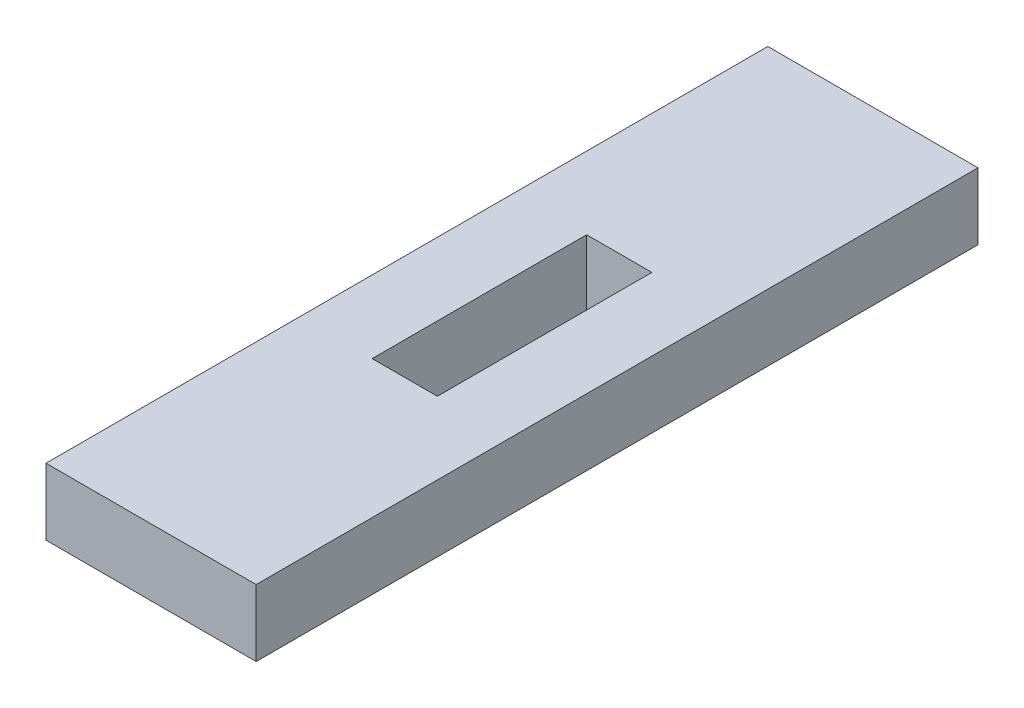
SolidWorks part; units mm, degrees
ref_plane "Front Plane" through (0, 0, 0) normal (0, 0, 1) x (1, 0, 0)
ref_plane "Top Plane" through (0, 0, 0) normal (0, 1, 0) x (1, 0, 0)
ref_plane "Right Plane" through (0, 0, 0) normal (1, 0, 0) x (0, 0, -1)
sketch "Sketch1" plane through (0, 0, 0) normal (0, 1, 0) x (1, 0, 0)
  line L5 (5.715, -18.796) -> (-5.715, -18.796)
  line L6 (5.715, -18.796) -> (5.715, 18.796)
  line L11 (5.715, 18.796) -> (-5.715, 18.796)
  line L12 (-5.715, -18.796) -> (-5.715, 18.796)
  line L13 (5.715, -18.796) -> (-5.715, 18.796) construction
  line L14 (5.715, 18.796) -> (-5.715, -18.796) construction
  line L15 (18.415, -63.246) -> (-18.415, -63.246)
  line L16 (18.415, -63.246) -> (18.415, 63.246)
  line L17 (18.415, 63.246) -> (-18.415, 63.246)
  line L18 (-18.415, -63.246) -> (-18.415, 63.246)
  line L19 (18.415, -63.246) -> (-18.415, 63.246) construction
  line L20 (18.415, 63.246) -> (-18.415, -63.246) construction
  point P0 (0, 0)
  point P6 (0, 0)
  dimension "D1" = 11.43
  dimension "D2" = 37.592
  dimension "D3" = 12.7
  dimension "D4" = 44.45
extrude "Boss-Extrude1" add sketch "Sketch1" along normal blind 11.684
equation "\"width\"= 0.455"
